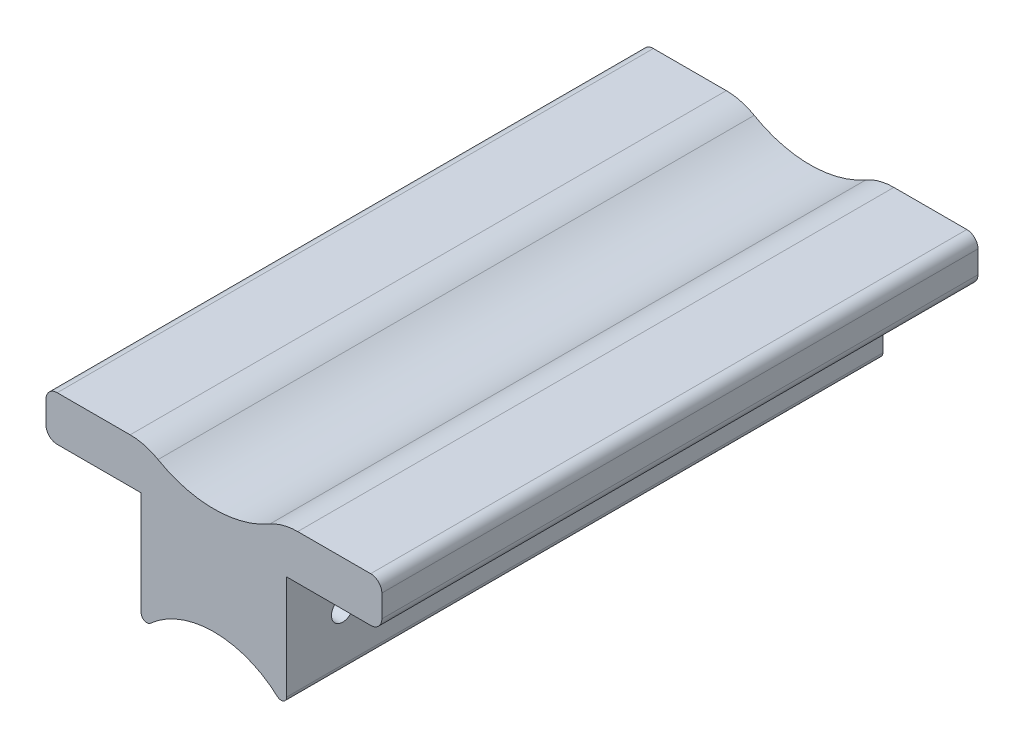
SolidWorks part; units mm, degrees
material "ABS"
ref_plane "Ebene vorne" through (0, 0, 0) normal (0, 0, 1) x (1, 0, 0)
ref_plane "Ebene oben" through (0, 0, 0) normal (0, 1, 0) x (1, 0, 0)
ref_plane "Ebene rechts" through (0, 0, 0) normal (1, 0, 0) x (0, 0, -1)
sketch "Skizze1" plane through (0, 0, 0) normal (0, 0, 1) x (1, 0, 0)
  line L0 (-30, 32) -> (-13, 32)
  line L1 (-13, 32) -> (-13, 10.9545)
  line L2 (-30, 32) -> (-30, 40)
  line L3 (-30, 40) -> (30, 40)
  line L4 (0, -55) -> (0, 55) construction
  line L5 (30, 32) -> (30, 40)
  line L6 (13, 32) -> (13, 10.9545)
  line L7 (30, 32) -> (13, 32)
  line L8 (-13, 17) -> (13, 17) construction
  circle A0 centre (0, 0) radius 17 construction
  arc A1 (-13, 10.9545) -> (13, 10.9545) centre (0, 0) cw
  point P14 (0, 40)
  dimension "D1" = 34
  dimension "D2" = 26
  dimension "D3" = 15
  dimension "D4" = 60
  dimension "D5" = 8
extrude "Aufsatz-Linear austragen1" add sketch "Skizze1" along normal blind 106.5
sketch "Skizze2" plane through (0, 0, 0) normal (0, 0, -1) x (-1, 0, 0)
  line L0 (-13, 32) -> (-30, 32) construction
  circle A0 centre (0, 56) radius 20
  dimension "D1" = 40
  dimension "D2" = 24
extrude "Schnitt-Linear austragen1" cut sketch "Skizze2" against normal through all contours A0
fillet "Verrundung1" radius 10 2 edges at (12, 40, 53.25) (-12, 40, 53.25)
fillet "Verrundung2" radius 2 4 edges at (-30, 32, 53.25) (-30, 40, 53.25) (30, 32, 53.25) (30, 40, 53.25)
fillet "Verrundung3" radius 1 2 edges at (13, 10.9545, 53.25) (-13, 10.9545, 53.25)
sketch "Skizze3" plane through (13, 0, 0) normal (1, 0, 0) x (0, 0, -1)
  line L0 (0, 13.4164) -> (0, 32) construction
  line L1 (-106.5, 13.4164) -> (-106.5, 32) construction
  circle A0 centre (-10, 22) radius 2
  circle A1 centre (-96.5, 22) radius 2
  dimension "D1" = 4
  dimension "D2" = 10
  dimension "D3" = 10
  dimension "D5" = 22
extrude "Schnitt-Linear austragen2" cut sketch "Skizze3" against normal through all
